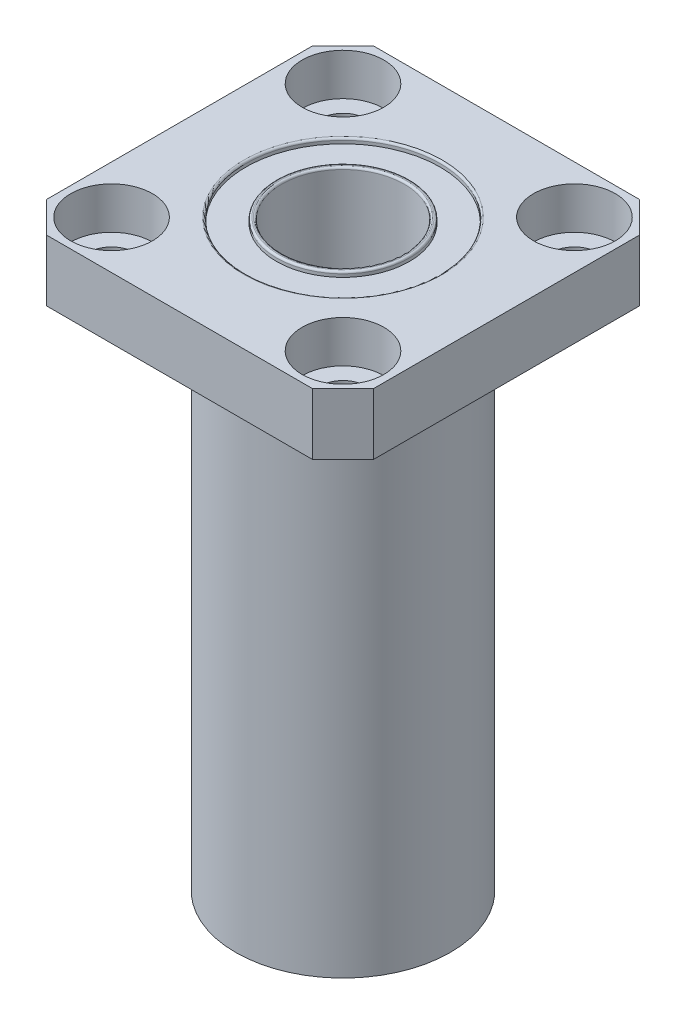
SolidWorks part; units mm, degrees
ref_plane "Alzado" through (0, 0, 0) normal (0, 0, 1) x (1, 0, 0)
ref_plane "Planta" through (0, 0, 0) normal (0, 1, 0) x (1, 0, 0)
ref_plane "Vista Lateral" through (0, 0, 0) normal (1, 0, 0) x (0, 0, -1)
sketch "Эскиз1" plane through (0, 0, 0) normal (0, 1, 0) x (1, 0, 0)
  circle A0 centre (0, 0) radius 10.5
  circle A1 centre (0, 0) radius 6
  dimension "D1" = 21
  dimension "D2" = 12
extrude "Saliente-Extruir1" add sketch "Эскиз1" along normal blind 57
sketch "Эскиз2" plane through (0, 57, 0) normal (0, 1, 0) x (1, 0, 0)
  line L1 (16, 16) -> (-16, 16)
  line L2 (16, 16) -> (16, -16)
  line L3 (16, -16) -> (-16, -16)
  line L4 (-16, 16) -> (-16, -16)
  line L5 (16, 16) -> (-16, -16) construction
  line L6 (16, -16) -> (-16, 16) construction
  circle A0 centre (0, 0) radius 6
  point P0 (0, 0)
  dimension "D3" = 12
  dimension "D1" = 32
  dimension "D2" = 32
extrude "Saliente-Extruir2" add sketch "Эскиз2" against normal blind 6
hole_wizard "Цековка для  винта с полукруглой головкой M41" positions "Эскиз4" profile "Эскиз3" counterbore size "M4" standard "Ansi Metric" end condition through all
sketch "Эскиз4" plane through (0, 57, 0) normal (0, 1, 0) x (1, 0, 0)
  line L0 (16, 16) -> (-16, -16) construction
  line L1 (-16, -16) -> (16, -16) construction
  line L2 (-16, 16) -> (-16, -16) construction
  line L4 (-16, 16) -> (16, -16) construction
  circle A0 centre (0, 0) radius 16
  point P0 (-11.3137, 11.3137)
  point P2 (11.3137, 11.3137)
  point P4 (11.3137, -11.3137)
  point P6 (-11.3137, -11.3137)
  dimension "D1" = 32
sketch "Эскиз3" plane through (-11.3137, 57, -11.3137) normal (1, 0, 0) x (0, 0, 1)
  line L0 (0, 0) -> (0, 57)
  line L1 (0, 57) -> (2.25, 57)
  line L3 (2.25, 57) -> (2.25, 4.1)
  line L4 (2.25, 4.1) -> (4, 4.1)
  line L5 (4, 4.1) -> (4, 0)
  line L7 (4, 0) -> (0, 0)
  line L11 (0, -6.35) -> (0, 107.95) construction
  dimension "Диаметр сквозного отверстия" = 4.5
  dimension "Глубина сквозного отверстия" = 57
  dimension "Диаметр цековки" = 8
  dimension "Глубина цековки" = 4.1
chamfer "Chaflán1" distance 3 angle 45 4 edges at (-16, 54, -16) (-16, 54, 16) (16, 54, -16) (16, 54, 16)
sketch "Эскиз5" plane through (0, 0, 0) normal (0, -1, 0) x (-1, 0, 0)
  circle A0 centre (0, 0) radius 9.5
  circle A1 centre (0, 0) radius 6.5
  dimension "D1" = 19
  dimension "D2" = 13
extrude "Cortar-Extruir2" cut sketch "Эскиз5" against normal blind 0.5
ref_plane "Plano1" through (0, 28.5, 0) normal (0, 1, 0) x (1, 0, 0)
mirror "Зеркальное отражение1" about plane through (0, 28.5, 0) normal (0, 1, 0) of "Cortar-Extruir2"
fillet "Redondeo1" radius 0.2 6 edges at (0, 0, -6.5) (0, 0, 6) (0, 57, 6) (0, 57, -6.5) (0, 57, -9.5) (0, 0, -9.5)
